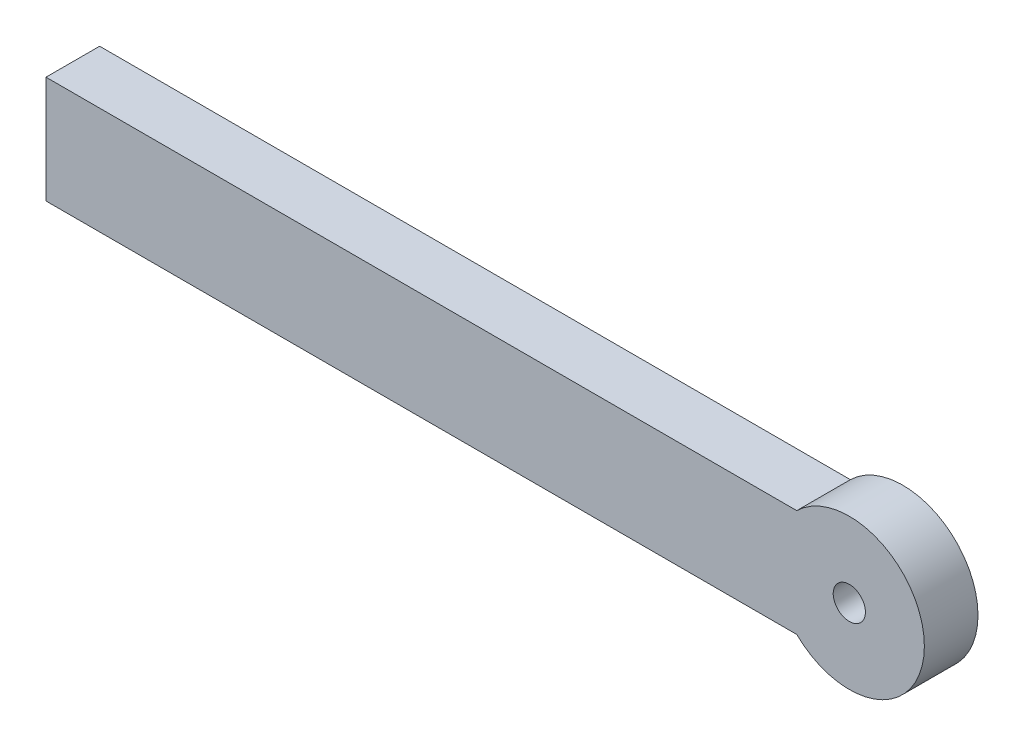
SolidWorks part; units mm, degrees
ref_plane "Front Plane" through (0, 0, 0) normal (0, 0, 1) x (1, 0, 0)
ref_plane "Top Plane" through (0, 0, 0) normal (0, 1, 0) x (1, 0, 0)
ref_plane "Right Plane" through (0, 0, 0) normal (1, 0, 0) x (0, 0, -1)
sketch "Sketch1" plane through (0, 0, 0) normal (0, 0, 1) x (1, 0, 0)
  line L0 (-74.899, 5) -> (-4.899, 5)
  line L1 (-74.899, -5) -> (-4.899, -5)
  line L2 (0, 0) -> (-44.4484, 0) construction
  line L3 (-74.899, 5) -> (-74.899, -5)
  arc A0 (-4.899, -5) -> (-4.899, 5) centre (0, 0) ccw
  circle A1 centre (0, 0) radius 1.5
  dimension "D1" = 14
  dimension "D6" = 3
  dimension "D2" = 5
  dimension "D3" = 5
  dimension "D4" = 70
  dimension "D5" = 70
extrude "Boss-Extrude1" add sketch "Sketch1" along normal blind 5
